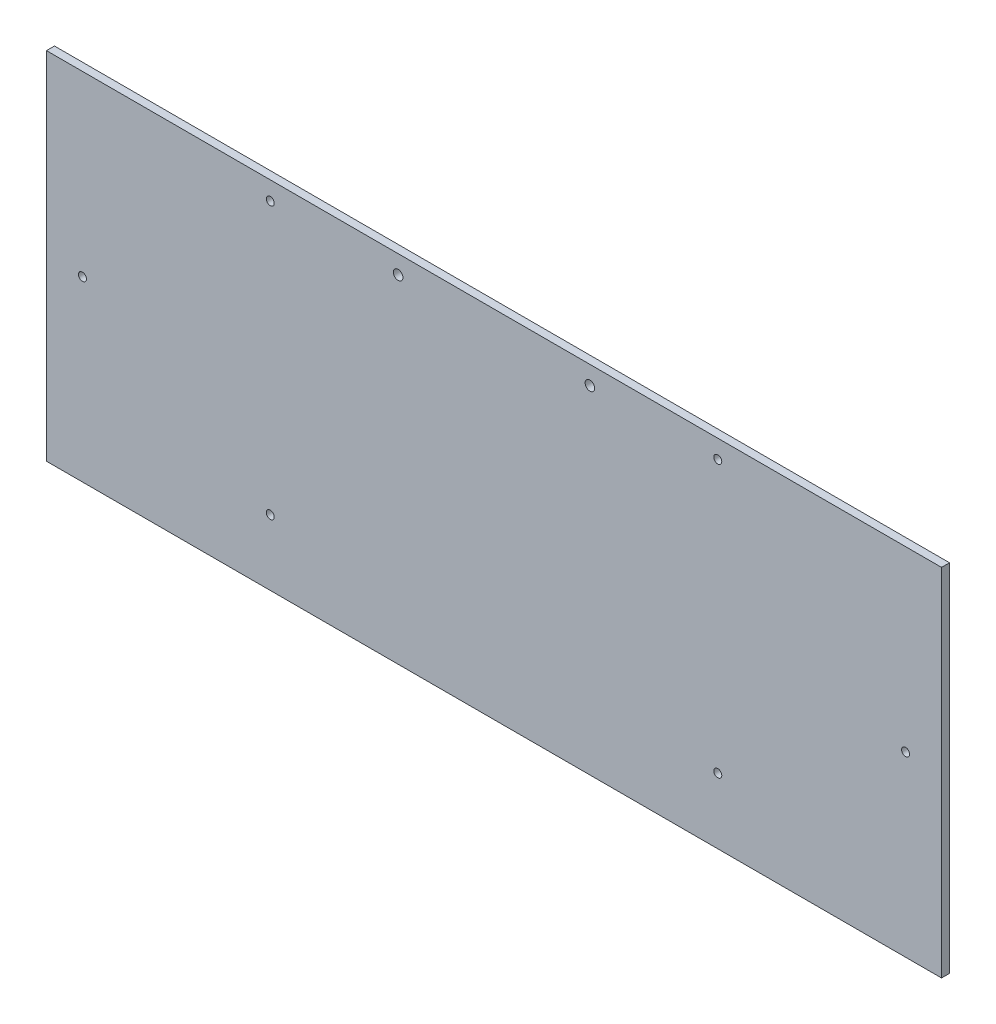
SolidWorks part; units mm, degrees
material "6061 合金"
ref_plane "前视基准面" through (0, 0, 0) normal (0, 0, 1) x (1, 0, 0)
ref_plane "上视基准面" through (0, 0, 0) normal (0, 1, 0) x (1, 0, 0)
ref_plane "右视基准面" through (0, 0, 0) normal (1, 0, 0) x (0, 0, -1)
other "Configuration Table"
sketch "草图1" plane through (0, 0, 0) normal (0, 0, 1) x (1, 0, 0)
  line L1 (-280, 222.5) -> (280, 222.5)
  line L2 (-280, 222.5) -> (-280, 0)
  line L3 (-280, 0) -> (280, 0)
  line L4 (280, 222.5) -> (280, 0)
  point P4 (0, 0)
  dimension "D1" = 560
  dimension "D2" = 222.5
extrude "凸台-拉伸1" add sketch "草图1" along normal blind 5
sketch "草图2" [suppressed] plane through (0, 0, 0) normal (0, 0, -1) x (-1, 0, 0)
  line L0 (0, 154) -> (0, 0) construction
  line L3 (-280, 154) -> (280, 154) construction
  line L4 (257.5, 132.5) -> (257.5, 32.5) construction
  line L5 (280, 154) -> (280, 0) construction
  line L6 (0, 142.5) -> (280, 142.5) construction
  line L7 (0, 22.5) -> (280, 22.5) construction
  line L8 (280, 0) -> (-280, 0) construction
  circle A6 centre (257.5, 77) radius 2.5
  circle A7 centre (140, 22.5) radius 2.5
  circle A8 centre (140, 142.5) radius 2.5
  circle A9 centre (60, 142.5) radius 3
  circle A10 centre (0, 22.5) radius 2.5 construction
  circle A11 centre (-60, 142.5) radius 3
  circle A12 centre (-140, 142.5) radius 2.5
  circle A13 centre (-140, 22.5) radius 2.5
  circle A14 centre (-257.5, 77) radius 2.5
  point P10 (280, 77)
  dimension "D1" = 5
  dimension "D2" = 22.5
  dimension "D3" = 11.5
  dimension "D5" = 6
  dimension "D6" = 120
  dimension "D4" = 22.5
extrude "切除-拉伸1" [suppressed] cut sketch "草图2" against normal through all both and the other way through all
sketch "草图3" [suppressed] plane through (0, 0, 5) normal (0, 0, 1) x (1, 0, 0)
  line L0 (0, 204) -> (0, 0) construction
  line L1 (280, 204) -> (-280, 204) construction
  line L2 (280, 0) -> (280, 204) construction
  line L3 (0, 22.5) -> (280, 22.5) construction
  line L4 (-280, 0) -> (280, 0) construction
  line L5 (0, 22.5) -> (-280, 22.5) construction
  circle A0 centre (60, 192.5) radius 3
  circle A1 centre (257.5, 102) radius 2.5
  circle A2 centre (140, 22.5) radius 2.5
  circle A3 centre (140, 192.5) radius 2.5
  circle A4 centre (-140, 192.5) radius 2.5
  circle A5 centre (-140, 22.5) radius 2.5
  circle A6 centre (-257.5, 102) radius 2.5
  circle A7 centre (-60, 192.5) radius 3
  point P10 (280, 102)
  dimension "D2" = 5
  dimension "D3" = 6
  dimension "D4" = 60
  dimension "D5" = 22.5
  dimension "D7" = 22.5
  dimension "D1" = 11.5
  dimension "D6" = 140
extrude "切除-拉伸2" [suppressed] cut sketch "草图3" against normal through all both and the other way through all
sketch "草图4" plane through (0, 0, 0) normal (0, 0, -1) x (-1, 0, 0)
  line L0 (0, 0) -> (0, 222.5) construction
  line L1 (-280, 222.5) -> (280, 222.5) construction
  line L2 (-280, 0) -> (-280, 222.5) construction
  line L4 (0, 211) -> (-280, 211) construction
  line L5 (0, 41) -> (-280, 41) construction
  circle A0 centre (-257.5, 111.25) radius 2.5
  circle A1 centre (-60, 211) radius 3
  circle A2 centre (-140, 211) radius 2.5
  circle A3 centre (-140, 41) radius 2.5
  circle A4 centre (257.5, 111.25) radius 2.5
  circle A5 centre (140, 211) radius 2.5
  circle A6 centre (60, 211) radius 3
  circle A7 centre (140, 41) radius 2.5
  point P8 (-280, 111.25)
  dimension "D1" = 22.5
  dimension "D2" = 5
  dimension "D3" = 60
  dimension "D4" = 6
extrude "切除-拉伸3" cut sketch "草图4" against normal through all both and the other way through all
